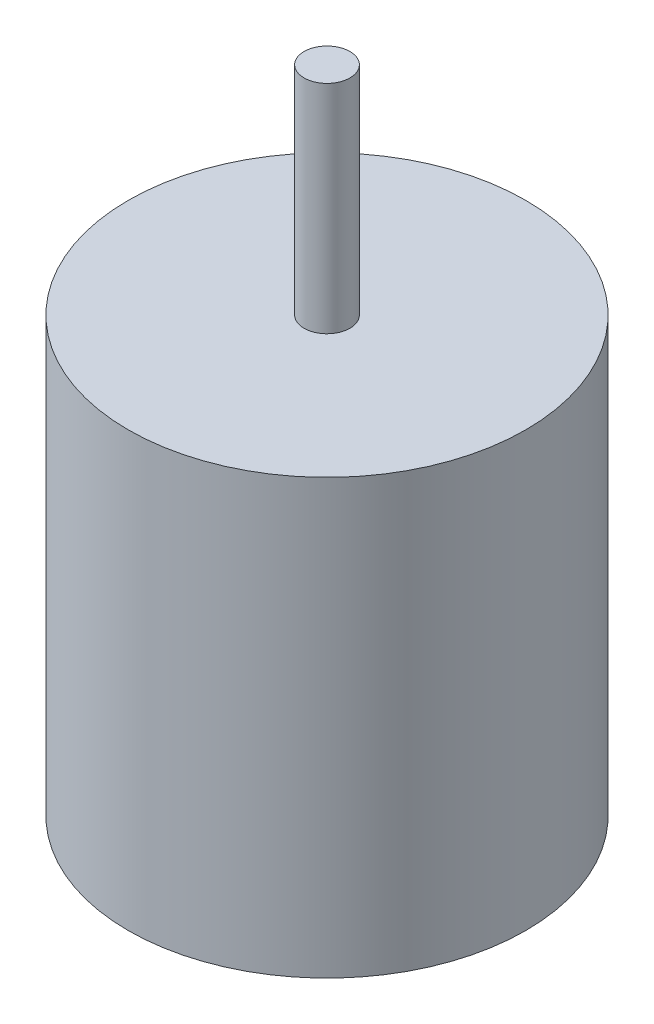
SolidWorks part; units mm, degrees
ref_plane "Front Plane" through (0, 0, 0) normal (0, 0, 1) x (1, 0, 0)
ref_plane "Top Plane" through (0, 0, 0) normal (0, 1, 0) x (1, 0, 0)
ref_plane "Right Plane" through (0, 0, 0) normal (1, 0, 0) x (0, 0, -1)
sketch "Sketch1" plane through (0, 0, 0) normal (0, 1, 0) x (1, 0, 0)
  circle A0 centre (0, 0) radius 13.75
  dimension "D1" = 27.5
extrude "Boss-Extrude1" add sketch "Sketch1" along normal blind 30
sketch "Sketch3" plane through (0, 30, 0) normal (0, 1, 0) x (1, 0, 0)
  circle A0 centre (0, 0) radius 1.585
  dimension "D1" = 3.17
extrude "Boss-Extrude2" add sketch "Sketch3" along normal blind 15
